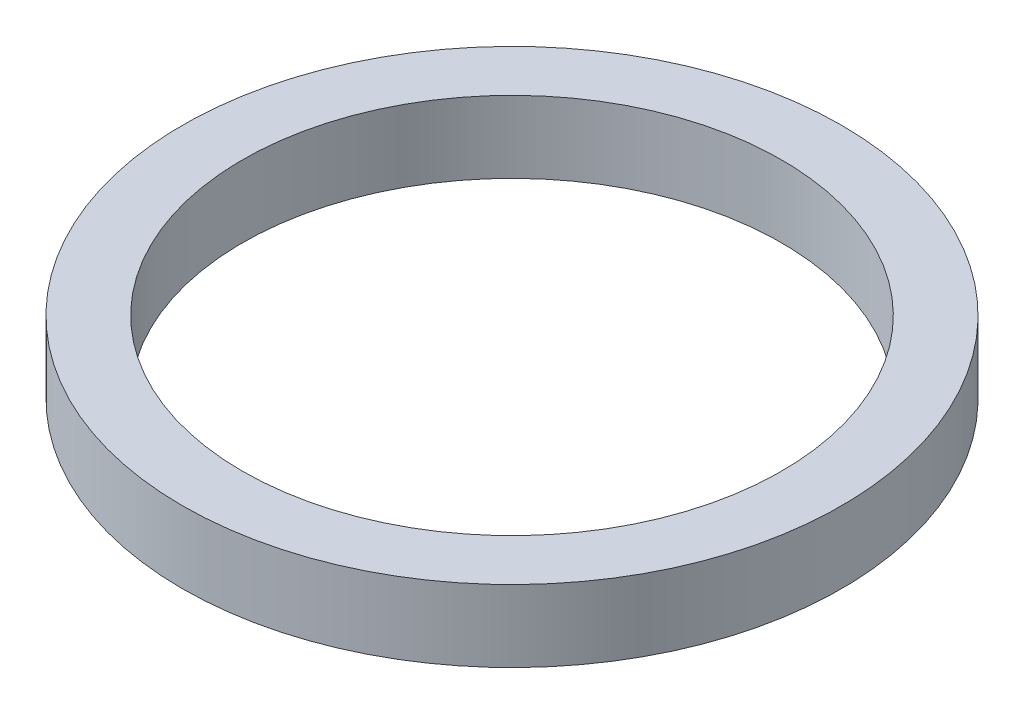
SolidWorks part; units mm, degrees
ref_plane "Front Plane" through (0, 0, 0) normal (0, 0, 1) x (1, 0, 0)
ref_plane "Top Plane" through (0, 0, 0) normal (0, 1, 0) x (1, 0, 0)
ref_plane "Right Plane" through (0, 0, 0) normal (1, 0, 0) x (0, 0, -1)
sketch "Sketch1" plane through (0, 0, 0) normal (0, 1, 0) x (1, 0, 0)
  circle A0 centre (0, 0) radius 22.5
  circle A1 centre (0, 0) radius 27.5
  dimension "D1" = 55
  dimension "D2" = 45
extrude "Boss-Extrude1" add sketch "Sketch1" along normal blind 6
equation "\"OD\"=55"
equation "\"D1@Sketch1\"=\"OD\""
equation "\"ID\"=45"
equation "\"D2@Sketch1\"=\"ID\""
equation "\"WIDTH\"=6"
equation "\"D1@Boss-Extrude1\"=\"WIDTH\""
